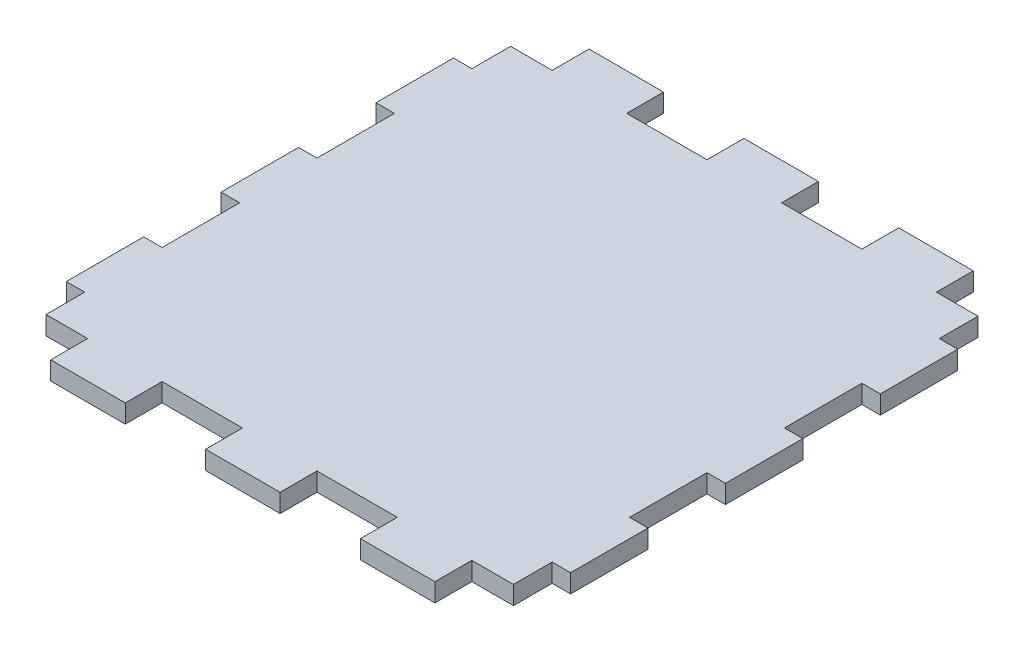
SolidWorks part; units mm, degrees
material "ABS"
ref_plane "Front Plane" through (0, 0, 0) normal (0, 0, 1) x (1, 0, 0)
ref_plane "Top Plane" through (0, 0, 0) normal (0, 1, 0) x (1, 0, 0)
ref_plane "Right Plane" through (0, 0, 0) normal (1, 0, 0) x (0, 0, -1)
ref_plane "Plane1" through (0, -26.565, 0) normal (0, 1, 0) x (1, 0, 0)
sketch "Sketch2" plane through (0, -26.565, 0) normal (0, 1, 0) x (1, 0, 0)
  line L0 (-40, 0) -> (-43.675, 0) construction
  line L1 (-43.675, 0) -> (-43.675, -6.35) construction
  line L2 (-43.675, -6.35) -> (-40, -6.35) construction
  line L3 (-40, -6.35) -> (-40, 0) construction
  line L4 (43.675, 0) -> (40, 0) construction
  line L5 (40, 0) -> (40, -6.35) construction
  line L6 (40, -6.35) -> (43.675, -6.35) construction
  line L7 (43.675, -6.35) -> (43.675, 0) construction
  line L8 (33.3333, 0) -> (20, 0) construction
  line L9 (20, 0) -> (20, -6.35) construction
  line L10 (-40, -26.3524) -> (-40, -39.6874)
  line L11 (33.3333, -6.35) -> (33.3333, 0) construction
  line L12 (6.6667, 0) -> (-6.6667, 0) construction
  line L13 (-6.6667, 0) -> (-6.6667, -6.35) construction
  line L14 (-40, -53.0224) -> (-40, -66.3573)
  line L15 (6.6667, -6.35) -> (6.6667, 0) construction
  line L16 (-20, 0) -> (-33.3333, 0) construction
  line L17 (-33.3333, 0) -> (-33.3333, -6.35) construction
  line L18 (-40, -79.6923) -> (-40, -86.3598)
  line L19 (-20, -6.35) -> (-20, 0) construction
  line L20 (-40, 0) -> (-43.675, 0) construction
  line L21 (-43.675, 0) -> (-43.675, -6.35) construction
  line L22 (-43.675, -6.35) -> (-40, -6.35) construction
  line L23 (-40, -6.35) -> (-40, 0) construction
  line L24 (43.675, 0) -> (40, 0) construction
  line L25 (40, 0) -> (40, -6.35) construction
  line L26 (40, -6.35) -> (43.675, -6.35) construction
  line L27 (43.675, -6.35) -> (43.675, 0) construction
  line L28 (33.3333, 0) -> (20, 0) construction
  line L29 (20, 0) -> (20, -6.35) construction
  line L31 (33.3333, -6.35) -> (33.3333, 0) construction
  line L32 (6.6667, 0) -> (-6.6667, 0) construction
  line L33 (-6.6667, 0) -> (-6.6667, -6.35) construction
  line L35 (6.6667, -6.35) -> (6.6667, 0) construction
  line L36 (-20, 0) -> (-33.3333, 0) construction
  line L37 (-33.3333, 0) -> (-33.3333, -6.35) construction
  line L39 (-20, -6.35) -> (-20, 0) construction
  line L40 (-33.3333, -3.175) -> (-33.0833, -3.175) construction
  line L41 (-40, -6.35) -> (-33.0833, -6.35)
  line L42 (-40, -6.35) -> (-40, -13.0175)
  line L46 (-33.0833, -6.35) -> (-33.0833, 0)
  line L47 (-33.0833, 0) -> (-20.25, 0)
  line L48 (-20.25, -6.35) -> (-20.25, 0)
  line L50 (-6.4167, -6.35) -> (-6.4167, 0)
  line L51 (-6.4167, 0) -> (6.4167, 0)
  line L52 (6.4167, -6.35) -> (6.4167, 0)
  line L54 (20.25, -6.35) -> (20.25, 0)
  line L55 (20.25, 0) -> (33.0833, 0)
  line L56 (33.0833, -6.35) -> (33.0833, 0)
  line L57 (-20, -3.175) -> (-20.25, -3.175) construction
  line L58 (-40, -53.0224) -> (-40, -46.3549) construction
  line L59 (-6.6667, -3.175) -> (-6.4167, -3.175) construction
  line L60 (-40, -46.3549) -> (-40, -39.6874) construction
  line L61 (6.6667, -3.175) -> (6.4167, -3.175) construction
  line L62 (20, -3.175) -> (20.25, -3.175) construction
  line L63 (0, 0) -> (0, -92.7098) construction
  line L64 (33.3333, -3.175) -> (33.0833, -3.175) construction
  line L65 (-20.25, -6.35) -> (-6.4167, -6.35)
  line L66 (6.4167, -6.35) -> (20.25, -6.35)
  line L67 (33.0833, -6.35) -> (40, -6.35)
  line L68 (40, -46.3549) -> (-40, -46.3549) construction
  line L69 (20.25, -86.3598) -> (20.25, -92.7098)
  line L70 (20.25, -92.7098) -> (33.0833, -92.7098)
  line L71 (33.0833, -86.3598) -> (33.0833, -92.7098)
  line L72 (33.0833, -86.3598) -> (40, -86.3598)
  line L73 (6.4167, -86.3598) -> (20.25, -86.3598)
  line L74 (6.4167, -86.3598) -> (6.4167, -92.7098)
  line L75 (-6.4167, -92.7098) -> (6.4167, -92.7098)
  line L76 (-6.4167, -86.3598) -> (-6.4167, -92.7098)
  line L77 (-20.25, -86.3598) -> (-6.4167, -86.3598)
  line L78 (-20.25, -86.3598) -> (-20.25, -92.7098)
  line L79 (-33.0833, -92.7098) -> (-20.25, -92.7098)
  line L80 (-33.0833, -86.3598) -> (-33.0833, -92.7098)
  line L81 (-40, -86.3598) -> (-33.0833, -86.3598)
  line L82 (-40, -13.0175) -> (-43.675, -13.0175)
  line L83 (-43.675, -13.0175) -> (-43.675, -26.3524)
  line L84 (-43.675, -26.3524) -> (-40, -26.3524)
  line L85 (-40, -39.6874) -> (-43.675, -39.6874)
  line L86 (-43.675, -39.6874) -> (-43.675, -53.0224)
  line L87 (-43.675, -53.0224) -> (-40, -53.0224)
  line L88 (-40, -79.6923) -> (-43.675, -79.6923)
  line L89 (-43.675, -79.6923) -> (-43.675, -66.3573)
  line L90 (-43.675, -66.3573) -> (-40, -66.3573)
  line L91 (-43.675, -66.3573) -> (-43.675, -53.0224) construction
  line L92 (-43.675, -39.6874) -> (-43.675, -26.3524) construction
  line L93 (-41.8375, -26.3524) -> (-41.8375, -33.0199) construction
  line L94 (-41.8375, -33.0199) -> (-41.8375, -39.6874) construction
  line L95 (-43.675, -79.6923) -> (-43.675, -86.3598) construction
  line L96 (-43.675, -86.3598) -> (-40, -86.3598) construction
  line L97 (-43.675, -6.35) -> (-43.675, -13.0175) construction
  line L98 (40, -53.0224) -> (40, -46.3549) construction
  line L99 (40, -53.0224) -> (40, -66.3573)
  line L100 (43.675, -6.35) -> (43.675, -13.0175) construction
  line L101 (43.675, -86.3598) -> (40, -86.3598) construction
  line L102 (43.675, -79.6923) -> (43.675, -86.3598) construction
  line L103 (41.8375, -33.0199) -> (41.8375, -39.6874) construction
  line L104 (41.8375, -26.3524) -> (41.8375, -33.0199) construction
  line L105 (43.675, -39.6874) -> (43.675, -26.3524) construction
  line L106 (43.675, -66.3573) -> (43.675, -53.0224) construction
  line L107 (40, -46.3549) -> (40, -39.6874) construction
  line L108 (43.675, -66.3573) -> (40, -66.3573)
  line L109 (43.675, -79.6923) -> (43.675, -66.3573)
  line L110 (40, -79.6923) -> (43.675, -79.6923)
  line L111 (43.675, -53.0224) -> (40, -53.0224)
  line L112 (43.675, -39.6874) -> (43.675, -53.0224)
  line L113 (40, -39.6874) -> (43.675, -39.6874)
  line L114 (43.675, -26.3524) -> (40, -26.3524)
  line L115 (43.675, -13.0175) -> (43.675, -26.3524)
  line L116 (40, -13.0175) -> (43.675, -13.0175)
  line L117 (40, -6.35) -> (40, -13.0175)
  line L118 (40, -79.6923) -> (40, -86.3598)
  line L119 (40, -26.3524) -> (40, -39.6874)
  dimension "D1" = 80.0098
  dimension "D2" = 0.25
extrude "Boss-Extrude1" add sketch "Sketch2" along normal offset from surface 0.25 and the other way offset from surface (1.5875 mm away) 0.25 contours L119 L114 L115 L116 L117 L67 L56 L55 L54 L66 L52 L51 L50 L65 L48 L47 L46 L41 L42 L82 L83 L84 L10 L85 L86 L87 L14 L90 L89 L88 L18 L81 L80 L79 L78 L77 L76 L75 L74 L73 L69 L70 L71 L72 L118 L110 L109 L108 L99 L111 L112
sketch "Sketch3" plane through (0, -24.9775, 0) normal (0, 1, 0) x (1, 0, 0)
  line L0 (-40, -26.3524) -> (-43.675, -26.3524) construction
  line L1 (-43.675, -13.0175) -> (-43.425, -13.0175)
  line L2 (-43.675, -13.0175) -> (-43.675, -26.3524)
  line L3 (-43.675, -26.3524) -> (-43.425, -26.3524)
  line L4 (-43.425, -13.0175) -> (-43.425, -26.3524)
  line L5 (-40, -53.0224) -> (-43.675, -53.0224) construction
  line L6 (-43.675, -39.6874) -> (-43.425, -39.6874)
  line L7 (-43.675, -39.6874) -> (-43.675, -53.0224)
  line L8 (-43.675, -53.0224) -> (-43.425, -53.0224)
  line L9 (-43.425, -39.6874) -> (-43.425, -53.0224)
  line L10 (-43.675, -79.6923) -> (-40, -79.6923) construction
  line L11 (-43.675, -66.3573) -> (-43.425, -66.3573)
  line L12 (-43.675, -66.3573) -> (-43.675, -79.6923)
  line L13 (-43.675, -79.6923) -> (-43.425, -79.6923)
  line L14 (-43.425, -66.3573) -> (-43.425, -79.6923)
  line L15 (40, -26.3524) -> (43.675, -26.3524) construction
  line L16 (43.675, -13.0175) -> (43.425, -13.0175)
  line L17 (43.675, -13.0175) -> (43.675, -26.3524)
  line L18 (43.675, -26.3524) -> (43.425, -26.3524)
  line L19 (43.425, -13.0175) -> (43.425, -26.3524)
  line L20 (40, -53.0224) -> (43.675, -53.0224) construction
  line L21 (43.675, -39.6874) -> (43.425, -39.6874)
  line L22 (43.675, -39.6874) -> (43.675, -53.0224)
  line L23 (43.675, -53.0224) -> (43.425, -53.0224)
  line L24 (43.425, -39.6874) -> (43.425, -53.0224)
  line L25 (43.675, -79.6923) -> (40, -79.6923) construction
  line L26 (43.675, -66.3573) -> (43.425, -66.3573)
  line L27 (43.675, -66.3573) -> (43.675, -79.6923)
  line L28 (43.675, -79.6923) -> (43.425, -79.6923)
  line L29 (43.425, -66.3573) -> (43.425, -79.6923)
  line L30 (-41.8375, -6.35) -> (-41.8375, 0) construction
  line L34 (-40, 0) -> (-43.675, 0)
  line L35 (-43.675, 0) -> (-43.675, -6.35)
  line L36 (-43.675, -6.35) -> (-40, -6.35)
  line L37 (-40, -6.35) -> (-40, 0)
  line L38 (-40, 0) -> (-43.675, 0) construction
  line L39 (-43.675, 0) -> (-43.675, -6.35) construction
  line L40 (-43.675, -6.35) -> (-40, -6.35) construction
  line L41 (-40, -6.35) -> (-40, 0) construction
  dimension "D2" = 1.5875
  dimension "D1" = 0
extrude "Cut-Extrude1" cut sketch "Sketch3" against normal through all
sketch "Sketch4" plane through (0, -24.9775, 0) normal (0, 1, 0) x (1, 0, 0)
  line L0 (-40, -26.3524) -> (-43.425, -26.3524) construction
  line L1 (-40, -13.0175) -> (-40.25, -13.0175)
  line L2 (-40, -13.0175) -> (-40, -6.35)
  line L3 (-40, -6.35) -> (-40.25, -6.35)
  line L4 (-40.25, -13.0175) -> (-40.25, -6.35)
  line L5 (-40, -39.6874) -> (-40.25, -39.6874)
  line L6 (-40, -39.6874) -> (-40, -26.3524)
  line L7 (-40, -26.3524) -> (-40.25, -26.3524)
  line L8 (-40.25, -39.6874) -> (-40.25, -26.3524)
  line L9 (-40, -53.0224) -> (-43.425, -53.0224) construction
  line L10 (-40, -66.3573) -> (-40.25, -66.3573)
  line L11 (-40, -66.3573) -> (-40, -53.0224)
  line L12 (-40, -53.0224) -> (-40.25, -53.0224)
  line L13 (-40.25, -66.3573) -> (-40.25, -53.0224)
  line L14 (40, -53.0224) -> (43.425, -53.0224) construction
  line L15 (-40, -79.6923) -> (-40.25, -79.6923)
  line L16 (-40, -79.6923) -> (-40, -86.3598)
  line L17 (-40, -86.3598) -> (-40.25, -86.3598)
  line L18 (-40.25, -79.6923) -> (-40.25, -86.3598)
  line L19 (40, -79.6923) -> (40.25, -79.6923)
  line L20 (40, -79.6923) -> (40, -86.3598)
  line L21 (40, -86.3598) -> (40.25, -86.3598)
  line L22 (40.25, -79.6923) -> (40.25, -86.3598)
  line L23 (40, -66.3573) -> (40.25, -66.3573)
  line L24 (40, -66.3573) -> (40, -53.0224)
  line L25 (40, -53.0224) -> (40.25, -53.0224)
  line L26 (40.25, -66.3573) -> (40.25, -53.0224)
  line L27 (40, -26.3524) -> (43.425, -26.3524) construction
  line L28 (40, -39.6874) -> (40.25, -39.6874)
  line L29 (40, -39.6874) -> (40, -26.3524)
  line L30 (40, -26.3524) -> (40.25, -26.3524)
  line L31 (40.25, -39.6874) -> (40.25, -26.3524)
  line L33 (40, -13.0175) -> (40.25, -13.0175)
  line L34 (40, -13.0175) -> (40, -6.35)
  line L35 (40, -6.35) -> (40.25, -6.35)
  line L36 (40.25, -13.0175) -> (40.25, -6.35)
  line L37 (-6.4167, -6.35) -> (-20.25, -6.35) construction
  line L39 (6.6667, -86.3598) -> (-6.6667, -86.3598) construction
  line L42 (-40, 0) -> (-43.675, 0)
  line L43 (-43.675, 0) -> (-43.675, -6.35)
  line L44 (-43.675, -6.35) -> (-40, -6.35)
  line L45 (-40, -6.35) -> (-40, 0)
  line L46 (-40, 0) -> (-43.675, 0) construction
  line L47 (-43.675, 0) -> (-43.675, -6.35) construction
  line L48 (-43.675, -6.35) -> (-40, -6.35) construction
  line L49 (-40, -6.35) -> (-40, 0) construction
  dimension "D2" = 0.25
  dimension "D1" = 0
extrude "Boss-Extrude2" add sketch "Sketch4" against normal up to surface (3.175 mm away) up to face at (0, -28.1525, 46.3549)
